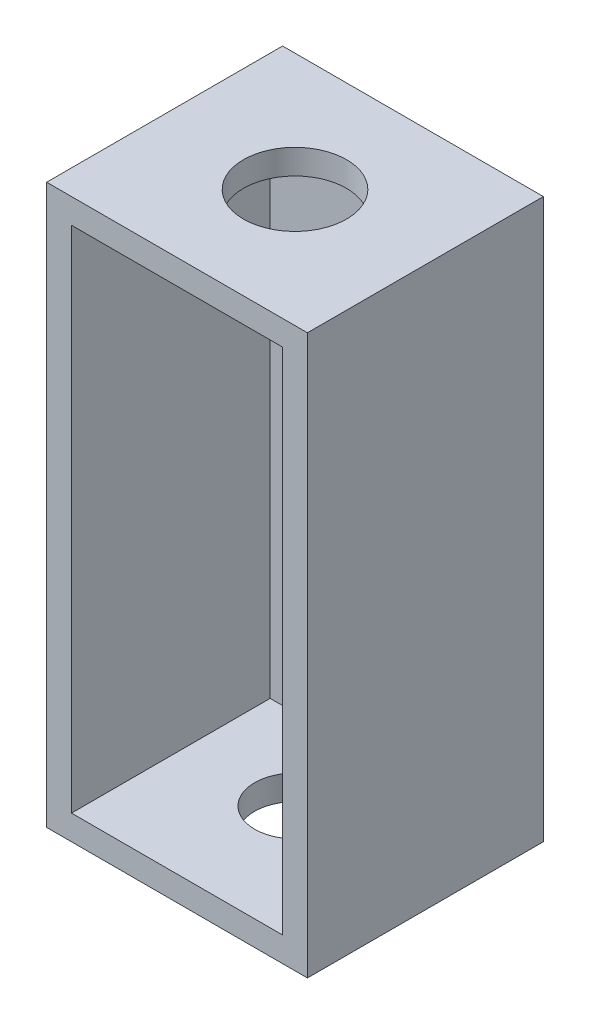
SolidWorks part; units mm, degrees
ref_plane "前视基准面" through (0, 0, 0) normal (0, 0, 1) x (1, 0, 0)
ref_plane "上视基准面" through (0, 0, 0) normal (0, 1, 0) x (1, 0, 0)
ref_plane "右视基准面" through (0, 0, 0) normal (1, 0, 0) x (0, 0, -1)
other "Configuration Table"
sketch "草图1" plane through (0, 0, 0) normal (0, 0, 1) x (1, 0, 0)
  line L0 (0, 0) -> (42, 0)
  line L1 (42, 0) -> (42, 90)
  line L2 (42, 90) -> (0, 90)
  line L3 (0, 90) -> (0, 0)
  dimension "width" = 42
  dimension "height" = 90
extrude "Housing_envelope" add sketch "草图1" along normal blind 38
sketch "草图2" plane through (0, 0, 38) normal (0, 0, 1) x (1, 0, 0)
  line L0 (4, 4) -> (38, 4)
  line L1 (38, 4) -> (38, 86)
  line L2 (38, 86) -> (4, 86)
  line L3 (4, 86) -> (4, 4)
  dimension "x0" = 4
  dimension "x1" = 38
  dimension "y0" = 4
  dimension "y2" = 86
extrude "Front_access_window" cut sketch "草图2" against normal blind 32
sketch "草图3" plane through (0, 90, 0) normal (0, 1, 0) x (1, 0, 0)
  circle A0 centre (21, -19) radius 6.5
  dimension "diameter" = 13
  dimension "x" = 21
  dimension "y" = 19
extrude "Axial_passage" cut sketch "草图3" against normal through all
sketch "草图4" plane through (0, 90, 0) normal (0, 1, 0) x (1, 0, 0)
  circle A0 centre (21, -19) radius 8.3
  dimension "diameter" = 16.6
  dimension "x" = 21
  dimension "y" = 19
extrude "D16_clearance" cut sketch "草图4" against normal blind 4.3
